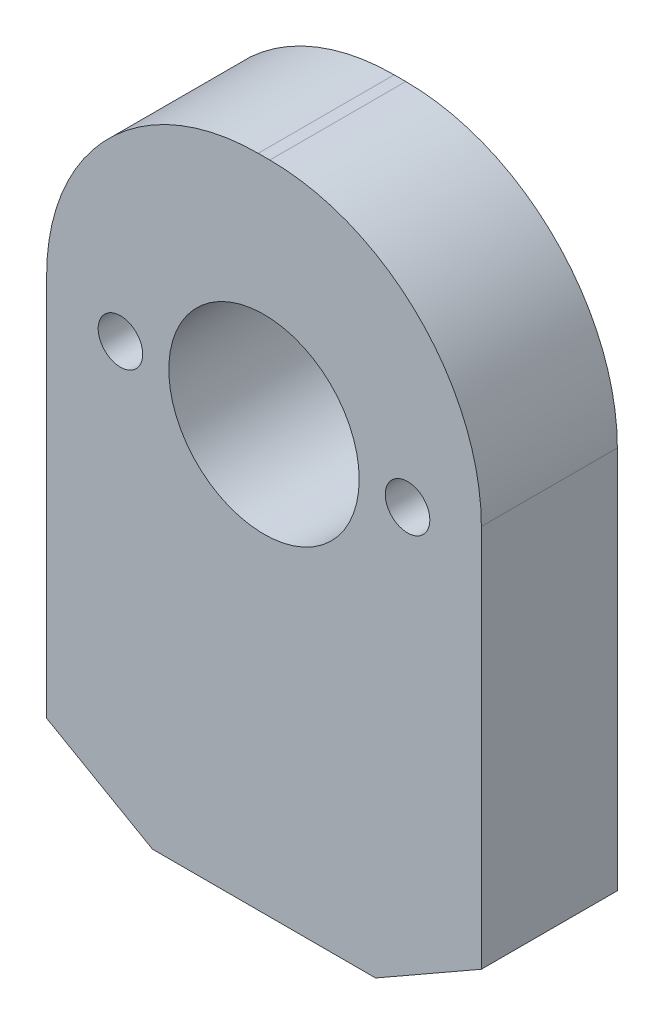
SolidWorks part; units mm, degrees
ref_plane "Front Plane" through (0, 0, 0) normal (0, 0, 1) x (1, 0, 0)
ref_plane "Top Plane" through (0, 0, 0) normal (0, 1, 0) x (1, 0, 0)
ref_plane "Right Plane" through (0, 0, 0) normal (1, 0, 0) x (0, 0, -1)
sketch "Sketch2" plane through (0, 0, 0) normal (0, 0, 1) x (1, 0, 0)
  line L0 (0, 4) -> (7, 0)
  line L1 (7, 0) -> (21.77, 0)
  line L2 (0, 4) -> (0, 29.38)
  line L3 (14, 43.38) -> (14.77, 43.38)
  line L4 (28.77, 4) -> (28.77, 29.38)
  line L5 (21.77, 0) -> (28.77, 4)
  circle A0 centre (14.385, 28.04) radius 6.3
  arc A1 (14.77, 43.38) -> (28.77, 29.38) centre (14.77, 29.38) cw
  arc A2 (0, 29.38) -> (14, 43.38) centre (14, 29.38) cw
  point P0 (0, 0)
  point P3 (28.77, 0)
  dimension "D4" = 12.6
  dimension "D2" = 14
  dimension "D1" = 28.77
  dimension "D3" = 15.34
  dimension "D5" = 7
  dimension "D6" = 4
  dimension "D7" = 7
  dimension "D8" = 4
extrude "Boss-Extrude1" add sketch "Sketch2" along normal blind 9
sketch "Sketch3" plane through (0, 0, 9) normal (0, 0, 1) x (1, 0, 0)
  circle A0 centre (14.385, 28.04) radius 9.5 construction
  circle A1 centre (4.885, 28.04) radius 1.475
  circle A2 centre (23.885, 28.04) radius 1.475
  dimension "D1" = 19
  dimension "D2" = 2.95
extrude "Cut-Extrude1" cut sketch "Sketch3" against normal blind 4
